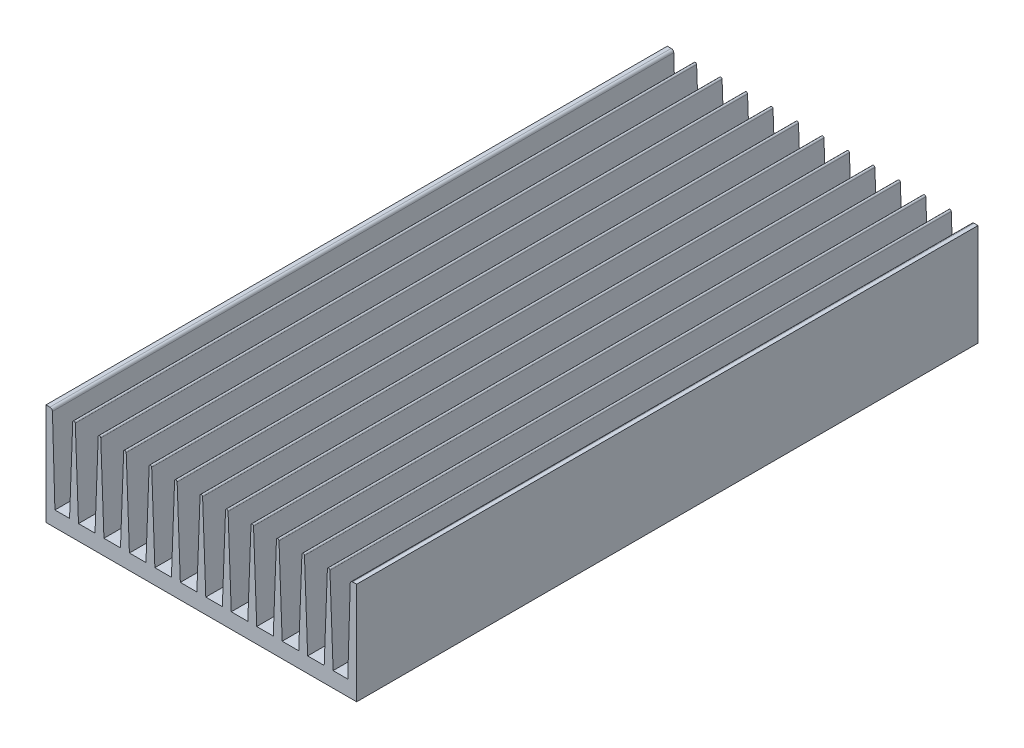
SolidWorks part; units mm, degrees
ref_plane "Спереди" through (0, 0, 0) normal (0, 0, 1) x (1, 0, 0)
ref_plane "Сверху" through (0, 0, 0) normal (0, 1, 0) x (1, 0, 0)
ref_plane "Справа" through (0, 0, 0) normal (1, 0, 0) x (0, 0, -1)
sketch "Эскиз1" plane through (0, 0, 0) normal (0, 0, 1) x (1, 0, 0)
  line L0 (0, 40) -> (1.529, 40)
  line L1 (0, 0) -> (122, 0)
  line L2 (2.5285, 39.0294) -> (3.5, 6)
  line L3 (0, 40) -> (0, 0)
  line L4 (122, 40) -> (122, 0)
  line L5 (61, 63.7127) -> (61, -22.2582) construction
  line L8 (122, 40) -> (120.471, 40)
  line L9 (119.4715, 39.0294) -> (118.5, 6)
  line L10 (3.5, 6) -> (118.5, 6)
  arc A0 (1.529, 40) -> (2.5285, 39.0294) centre (1.529, 39) cw
  arc A2 (120.471, 40) -> (119.4715, 39.0294) centre (120.471, 39) ccw
  point P18 (119.5, 40)
  dimension "D9" = 1
  dimension "D1" = 122
  dimension "D2" = 6
  dimension "D3" = 40
  dimension "D4" = 3.5
  dimension "D7" = 2.5
extrude "Вытянуть1" add sketch "Эскиз1" along normal blind 244
sketch "Эскиз2" plane through (0, 0, 244) normal (0, 0, 1) x (1, 0, 0)
  line L0 (118.5, 6) -> (3.5, 6) construction
  line L1 (10.5, 39.5) -> (9.25, 6)
  line L2 (11, 39.5) -> (11, 22.5548) construction
  line L3 (11.5, 39.5) -> (12.75, 6)
  line L4 (9.25, 6) -> (12.75, 6)
  line L6 (0, 40) -> (0, 0) construction
  arc A0 (10.5, 39.5) -> (11.5, 39.5) centre (11, 39.5) cw
  dimension "D1" = 34
  dimension "D3" = 0.5
  dimension "D2" = 3.5
  dimension "D4" = 11
  dimension "D5" = 1
extrude "Вытянуть3" add sketch "Эскиз2" against normal blind 244
pattern_curve "Кривая1" of "Вытянуть3" along edge at (61, 0, 0) parameters "D1"=11, "D3"=10, "D2"=1, "D4"=50
sketch "Эскиз3" plane through (0, 0, 0) normal (0, -1, 0) x (1, 0, 0)
  line L0 (-14.0506, 236) -> (137.5079, 236) construction
  line L1 (0, 244) -> (122, 244) construction
  line L2 (0, 244) -> (0, 0) construction
  line L3 (-46.7511, 122) -> (151.4312, 122) construction
  line L4 (0, 0) -> (122, 0) construction
  circle A0 centre (26, 236) radius 2.25
  circle A1 centre (96, 236) radius 2.25
  circle A2 centre (96, 8) radius 2.25
  circle A3 centre (26, 8) radius 2.25
  dimension "D2" = 70
  dimension "D4" = 4.5
  dimension "D1" = 8
  dimension "D3" = 26
extrude "Вырез-Вытянуть1" cut sketch "Эскиз3" against normal blind 6
sketch "Эскиз4" plane through (147.9336, 0, 237.9463) normal (0, -1, 0) x (-1, 0, 0)
  line L0 (85.9336, 82.9463) -> (85.9336, 217.9463) construction
  line L1 (46.9288, 130.4463) -> (-4.4456, 130.4463) construction
  line L3 (147.9336, 237.9463) -> (25.9336, 237.9463) construction
  line L4 (25.9336, -6.0537) -> (25.9336, 237.9463) construction
  circle A0 centre (42.4336, 130.4463) radius 1.6
  circle A2 centre (85.9336, 217.9463) radius 1.6
  circle A3 centre (85.9336, 82.9463) radius 1.6
  dimension "D3" = 87.5
  dimension "D1" = 60
  dimension "D5" = 135
  dimension "D6" = 3.2
  dimension "D2" = 43.5
  dimension "D4" = 20
extrude "Вырез-Вытянуть2" cut sketch "Эскиз4" against normal blind 6
cosmetic thread "Условное изображение резьбы5" parameters "D2"=4
cosmetic thread "Условное изображение резьбы6" parameters "D2"=4
cosmetic thread "Условное изображение резьбы7" parameters "D2"=4
